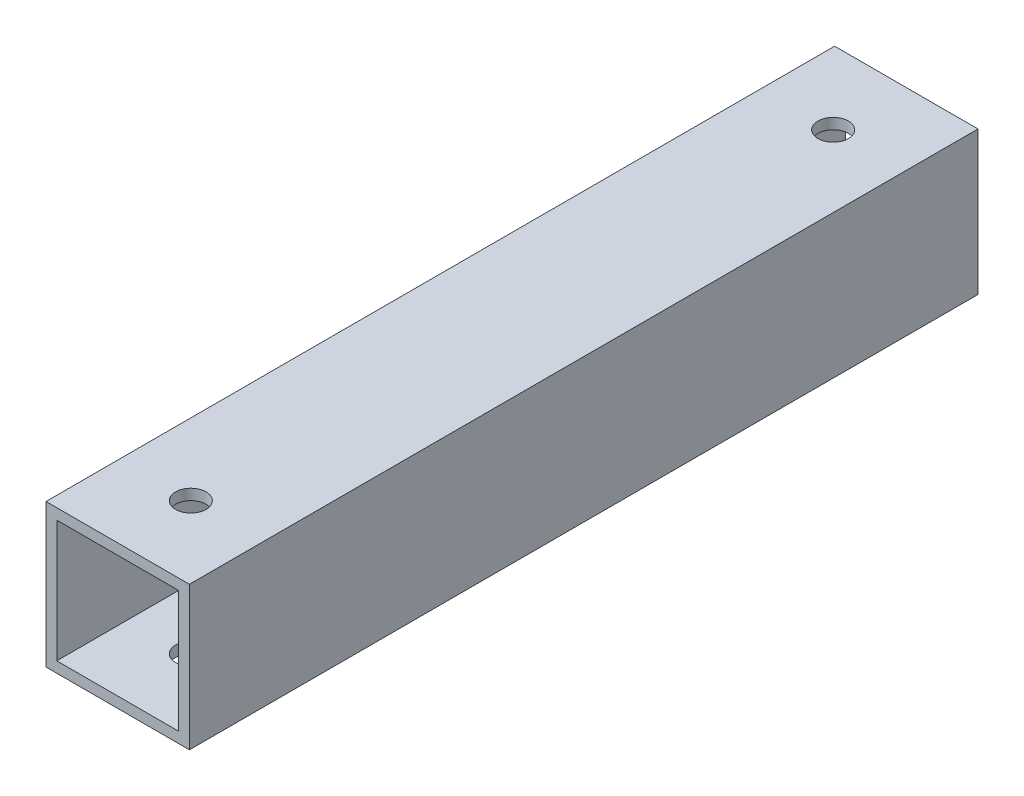
SolidWorks part; units mm, degrees
ref_plane "Front Plane" through (0, 0, 0) normal (0, 0, 1) x (1, 0, 0)
ref_plane "Top Plane" through (0, 0, 0) normal (0, 1, 0) x (1, 0, 0)
ref_plane "Right Plane" through (0, 0, 0) normal (1, 0, 0) x (0, 0, -1)
sketch "Sketch1" plane through (0, 0, 0) normal (0, 0, 1) x (1, 0, 0)
  line L0 (-8.5, -8.5) -> (8.5, -8.5)
  line L1 (-10, -10) -> (10, -10)
  line L2 (-10, -10) -> (-10, 10)
  line L3 (-10, 10) -> (10, 10)
  line L4 (10, -10) -> (10, 10)
  line L5 (-10, -10) -> (10, 10) construction
  line L6 (-10, 10) -> (10, -10) construction
  line L7 (8.5, -8.5) -> (8.5, 8.5)
  line L8 (-8.5, 8.5) -> (8.5, 8.5)
  line L9 (-8.5, -8.5) -> (-8.5, 8.5)
  point P0 (0, 0)
  dimension "D1" = 20
  dimension "D3" = 20
  dimension "D2" = 1.5
extrude "Boss-Extrude1" add sketch "Sketch1" against normal blind 110
sketch "Sketch2" plane through (0, 10, 0) normal (0, 1, 0) x (1, 0, 0)
  line L0 (10, 0) -> (-10, 0) construction
  line L1 (-10, 55) -> (10, 55) construction
  line L2 (-10, 110) -> (-10, 0) construction
  line L3 (10, 110) -> (10, 0) construction
  circle A0 centre (0, 10.2) radius 2.125
  circle A1 centre (0, 99.8) radius 2.125
  dimension "D1" = 4.25
  dimension "D2" = 10.2
extrude "Cut-Extrude1" cut sketch "Sketch2" against normal through all
